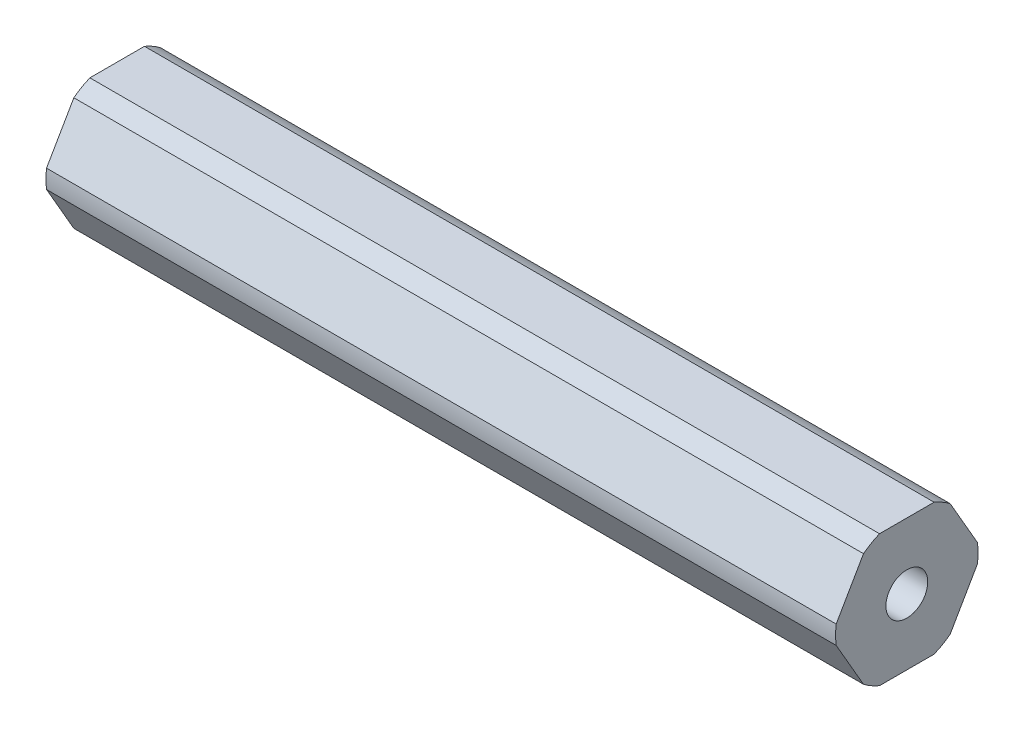
SolidWorks part; units mm, degrees
material "6061-T6 (SS)"
ref_plane "Front Plane" through (0, 0, 0) normal (0, 0, 1) x (1, 0, 0)
ref_plane "Top Plane" through (0, 0, 0) normal (0, 1, 0) x (1, 0, 0)
ref_plane "Right Plane" through (0, 0, 0) normal (1, 0, 0) x (0, 0, -1)
sketch "Sketch1" plane through (0, 0, 0) normal (1, 0, 0) x (0, 0, -1)
  line L1 (7.3323, 0) -> (3.6662, 6.35)
  line L2 (3.6662, 6.35) -> (-3.6662, 6.35)
  line L3 (-3.6662, 6.35) -> (-7.3323, 0)
  line L4 (-7.3323, 0) -> (-3.6662, -6.35)
  line L5 (-3.6662, -6.35) -> (3.6662, -6.35)
  line L6 (3.6662, -6.35) -> (7.3323, 0)
  circle A0 centre (0, 0) radius 6.35 construction
  circle A1 centre (0, 0) radius 6.875
  circle A2 centre (0, 0) radius 2.0193
  dimension "D1" = 12.7
  dimension "D2" = 13.75
  dimension "D3" = 4.0386
extrude "Boss-Extrude1" add sketch "Sketch1" along normal mid plane 76.2 contours L1 A1 L2 L3 L4 L5 L6 A2
equation "\"D2@Sketch1\"=13.75MM"
equation "\"D3@Sketch1\"=.159"
